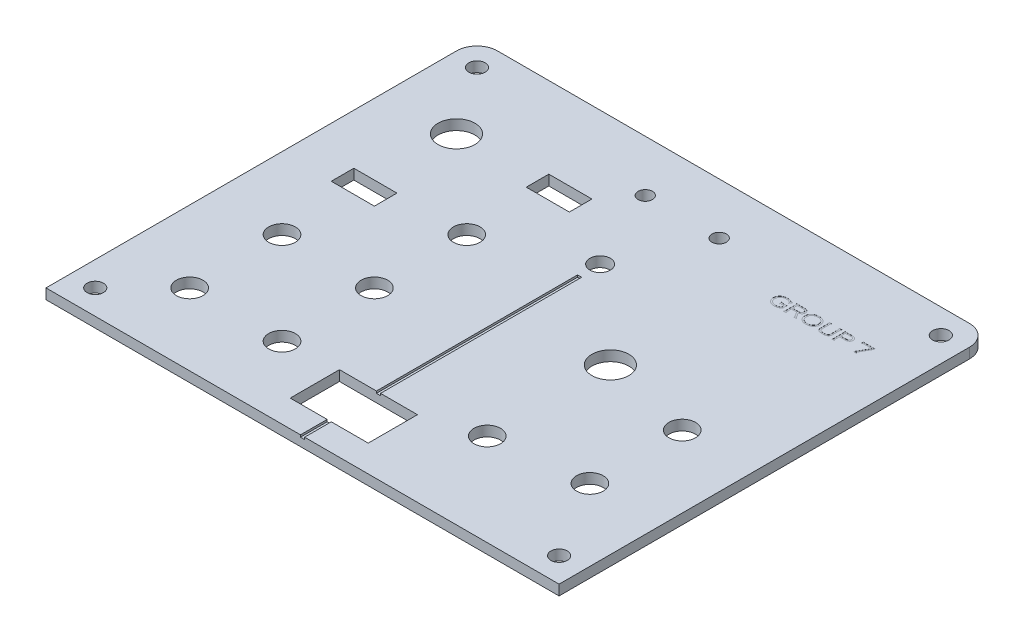
SolidWorks part; units mm, degrees
ref_plane "Front Plane" through (0, 0, 0) normal (0, 0, 1) x (1, 0, 0)
ref_plane "Top Plane" through (0, 0, 0) normal (0, 1, 0) x (1, 0, 0)
ref_plane "Right Plane" through (0, 0, 0) normal (1, 0, 0) x (0, 0, -1)
sketch "Sketch1" plane through (0, 0, 0) normal (0, 1, 0) x (1, 0, 0)
  line L1 (-62.5, 52.5) -> (62.5, 52.5)
  line L2 (-62.5, 52.5) -> (-62.5, -52.5)
  line L3 (-62.5, -52.5) -> (62.5, -52.5)
  line L4 (62.5, 52.5) -> (62.5, -52.5)
  line L5 (-62.5, 52.5) -> (62.5, -52.5) construction
  line L6 (-62.5, -52.5) -> (62.5, 52.5) construction
  point P0 (0, 0)
extrude "Boss-Extrude1" add sketch "Sketch1" along normal blind 2.5
sketch "Sketch2" plane through (0, 2.5, 0) normal (0, 1, 0) x (1, 0, 0)
  circle A0 centre (-45, 30) radius 4.5
  point P2 (0, 0)
  point P3 (0, 0)
  point P4 (0, 0)
  point P5 (0, 0)
  point P6 (0, 0)
  point P7 (0, 0)
  point P8 (0, 0)
extrude "Cut-Extrude2" cut sketch "Sketch2" against normal blind 10
sketch "Sketch3" plane through (0, 2.5, 0) normal (0, 1, 0) x (1, 0, 0)
  circle A0 centre (-45, -35) radius 3.25
  point P2 (0, 0)
  point P3 (0, 0)
extrude "Cut-Extrude3" cut sketch "Sketch3" against normal blind 10
sketch "Sketch4" plane through (0, 2.5, 0) normal (0, 1, 0) x (1, 0, 0)
  line L1 (-25.25, 32.75) -> (-14.75, 32.75)
  line L2 (-25.25, 32.75) -> (-25.25, 27.25)
  line L3 (-25.25, 27.25) -> (-14.75, 27.25)
  line L4 (-14.75, 32.75) -> (-14.75, 27.25)
  line L5 (-25.25, 32.75) -> (-14.75, 27.25) construction
  line L6 (-25.25, 27.25) -> (-14.75, 32.75) construction
  point P0 (-20, 30)
  point P5 (0, 0)
  point P6 (0, 0)
  point P7 (0, 0)
  point P8 (0, 0)
  point P9 (0, 0)
  point P10 (0, 0)
extrude "Cut-Extrude4" cut sketch "Sketch4" against normal blind 20
sketch "Sketch5" plane through (0, 2.5, 0) normal (0, 1, 0) x (1, 0, 0)
  circle A0 centre (-22.5, 10) radius 3.25
  circle A1 centre (-22.5, -12.5) radius 3.25
  circle A2 centre (-22.5, -35) radius 3.25
  point P6 (0, 0)
  point P7 (0, 0)
  point P8 (0, 0)
  point P9 (0, 0)
  point P10 (0, 0)
  point P11 (0, 0)
extrude "Cut-Extrude5" cut sketch "Sketch5" against normal blind 10
sketch "Sketch6" plane through (0, 2.5, 0) normal (0, 1, 0) x (1, 0, 0)
  circle A0 centre (22.5, 0) radius 4.5
  point P2 (0, 0)
extrude "Cut-Extrude6" cut sketch "Sketch6" against normal blind 10
sketch "Sketch7" plane through (0, 2.5, 0) normal (0, 1, 0) x (1, 0, 0)
  circle A0 centre (22.5, -30) radius 3.25
  point P2 (0, 0)
  point P3 (0, 0)
extrude "Cut-Extrude7" cut sketch "Sketch7" against normal blind 10
sketch "Sketch8" plane through (0, 2.5, 0) normal (0, 1, 0) x (1, 0, 0)
  line L1 (-50.25, 10.25) -> (-39.75, 10.25)
  line L2 (-50.25, 10.25) -> (-50.25, 4.75)
  line L3 (-50.25, 4.75) -> (-39.75, 4.75)
  line L4 (-39.75, 10.25) -> (-39.75, 4.75)
  line L5 (-50.25, 10.25) -> (-39.75, 4.75) construction
  line L6 (-50.25, 4.75) -> (-39.75, 10.25) construction
  point P0 (-45, 7.5)
  point P5 (0, 0)
  point P6 (0, 0)
  point P7 (0, 0)
  point P8 (0, 0)
  point P9 (0, 0)
  point P10 (0, 0)
  point P11 (0, 0)
  point P12 (0, 0)
extrude "Cut-Extrude8" cut sketch "Sketch8" against normal blind 10
sketch "Sketch9" plane through (0, 2.5, 0) normal (0, 1, 0) x (1, 0, 0)
  circle A0 centre (45, -5) radius 3.25
  circle A1 centre (45, -27.5) radius 3.25
  point P4 (0, 0)
  point P5 (0, 0)
  point P6 (0, 0)
  point P7 (0, 0)
  point P8 (0, 0)
extrude "Cut-Extrude9" cut sketch "Sketch9" against normal blind 10
sketch "Sketch15" plane through (0, 2.5, 0) normal (0, 1, 0) x (1, 0, 0)
  line L1 (-0.5, 15) -> (0.5, 15)
  line L2 (-0.5, 15) -> (-0.5, -55)
  line L3 (-0.5, -55) -> (0.5, -55)
  line L4 (0.5, 15) -> (0.5, -55)
  line L5 (-0.5, 15) -> (0.5, -55) construction
  line L6 (-0.5, -55) -> (0.5, 15) construction
  point P0 (0, -20)
extrude "Cut-Extrude11" cut sketch "Sketch15" against normal blind 0.5
sketch "Sketch19" plane through (0, 2.5, 0) normal (0, 1, 0) x (1, 0, 0)
  circle A0 centre (-56.5, 46.5) radius 2
extrude "Cut-Extrude13" cut sketch "Sketch19" against normal blind 10
mirror "Mirror1" about plane through (0, 0, 0) normal (0, 0, 1) of "Cut-Extrude13"
mirror "Mirror2" about plane through (0, 0, 0) normal (1, 0, 0) of "Cut-Extrude13"
mirror "Mirror3" about plane through (0, 0, 0) normal (0, 0, 1) of "Mirror2"
sketch "Sketch20" plane through (0, 2.5, 0) normal (0, 1, 0) x (1, 0, 0)
  circle A0 centre (0, 20) radius 2.5
extrude "Cut-Extrude14" cut sketch "Sketch20" against normal blind 10
sketch "Sketch21" plane through (0, 2.5, 0) normal (0, 1, 0) x (1, 0, 0)
  circle A0 centre (9, 40) radius 1.75
  point P2 (0, 0)
extrude "Cut-Extrude15" cut sketch "Sketch21" against normal blind 10
mirror "Mirror4" about plane through (0, 0, 0) normal (1, 0, 0) of "Cut-Extrude15"
fillet "Fillet1" radius 5 1 edges at (62.5, 1.25, -52.5)
fillet "Fillet2" radius 5 1 edges at (-62.5, 1.25, -52.5)
sketch "Sketch26" plane through (0, 2.5, 0) normal (0, 1, 0) x (1, 0, 0)
  line L1 (-9.5, -46) -> (9.5, -46)
  line L2 (-9.5, -46) -> (-9.5, -34)
  line L3 (-9.5, -34) -> (9.5, -34)
  line L4 (9.5, -46) -> (9.5, -34)
  line L5 (-9.5, -46) -> (9.5, -34) construction
  line L6 (-9.5, -34) -> (9.5, -46) construction
  point P0 (0, -40)
  point P5 (0, 0)
extrude "Cut-Extrude16" cut sketch "Sketch26" against normal blind 10
sketch "Sketch27" plane through (0, 2.5, 0) normal (0, 1, 0) x (1, 0, 0)
  circle A0 centre (-45, -12.5) radius 3.25
  point P2 (0, 0)
  point P3 (0, 0)
  point P4 (0, 0)
  point P5 (0, 0)
  point P6 (0, 0)
  point P7 (0, 0)
  point P8 (0, 0)
  point P9 (0, 0)
  point P10 (0, 0)
  point P11 (0, 0)
  point P12 (0, 0)
  point P13 (0, 0)
  point P14 (0, 0)
  point P15 (0, 0)
  point P16 (0, 0)
  point P17 (0, 0)
  point P18 (0, 0)
extrude "Cut-Extrude17" cut sketch "Sketch27" against normal blind 10
sketch "Sketch28" plane through (0, 2.5, 0) normal (0, 1, 0) x (1, 0, 0)
  text T0 "GROUP 7" font "Copperplate Gothic Light" height 3.175
extrude "Cut-Extrude18" cut sketch "Sketch28" against normal blind 0.0254
